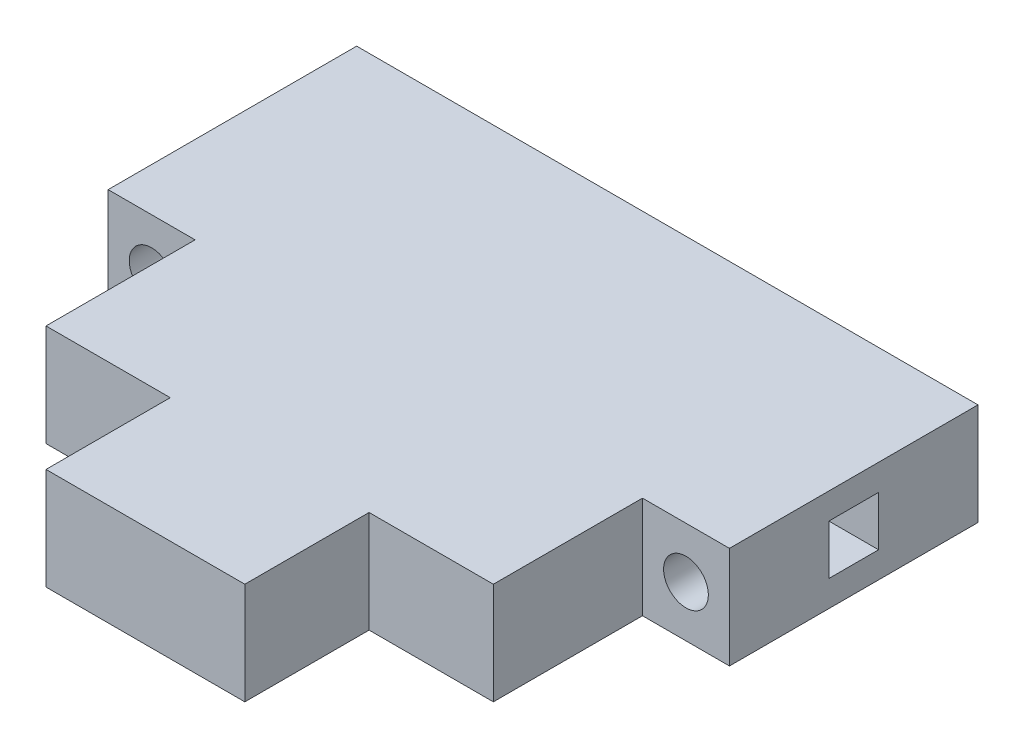
SolidWorks part; units mm, degrees
ref_plane "Front Plane" through (0, 0, 0) normal (0, 0, 1) x (1, 0, 0)
ref_plane "Top Plane" through (0, 0, 0) normal (0, 1, 0) x (1, 0, 0)
ref_plane "Right Plane" through (0, 0, 0) normal (1, 0, 0) x (0, 0, -1)
sketch "Sketch1" plane through (0, 0, 0) normal (0, 1, 0) x (1, 0, 0)
  line L0 (-25, 0) -> (25, 0)
  line L1 (25, 0) -> (25, -20)
  line L2 (25, -20) -> (18, -20)
  line L3 (18, -20) -> (18, -32)
  line L4 (18, -32) -> (8, -32)
  line L5 (8, -32) -> (8, -42)
  line L6 (8, -42) -> (-8, -42)
  line L7 (-8, -42) -> (-8, -32)
  line L8 (-8, -32) -> (-18, -32)
  line L9 (-18, -32) -> (-18, -20)
  line L10 (-18, -20) -> (-25, -20)
  line L11 (-25, -20) -> (-25, 0)
extrude "Body" add sketch "Sketch1" along normal blind 8.2
ref_plane "Plane_z20" through (0, 0, 20) normal (0, 0, 1) x (1, 0, 0)
sketch "Sketch2" plane through (0, 0, 20) normal (0, 0, 1) x (1, 0, 0)
  circle A0 centre (-21.5, 4.1) radius 1.8
  circle A1 centre (21.5, 4.1) radius 1.8
extrude "Screws" cut sketch "Sketch2" against normal blind 6
ref_plane "Plane_x25" through (25, 0, 0) normal (1, 0, 0) x (0, 0, -1)
sketch "Sketch3" plane through (25, 0, 0) normal (1, 0, 0) x (0, 0, -1)
  line L1 (-8, 2.1) -> (-12, 2.1)
  line L2 (-8, 2.1) -> (-8, 6.1)
  line L3 (-8, 6.1) -> (-12, 6.1)
  line L4 (-12, 2.1) -> (-12, 6.1)
extrude "Wire_R" cut sketch "Sketch3" against normal blind 8
ref_plane "Plane_xm25" through (-25, 0, 0) normal (1, 0, 0) x (0, 0, -1)
sketch "Sketch4" plane through (-25, 0, 0) normal (1, 0, 0) x (0, 0, -1)
  line L1 (-8, 2.1) -> (-12, 2.1)
  line L2 (-8, 2.1) -> (-8, 6.1)
  line L3 (-8, 6.1) -> (-12, 6.1)
  line L4 (-12, 2.1) -> (-12, 6.1)
extrude "Wire_L" cut sketch "Sketch4" along normal blind 8
